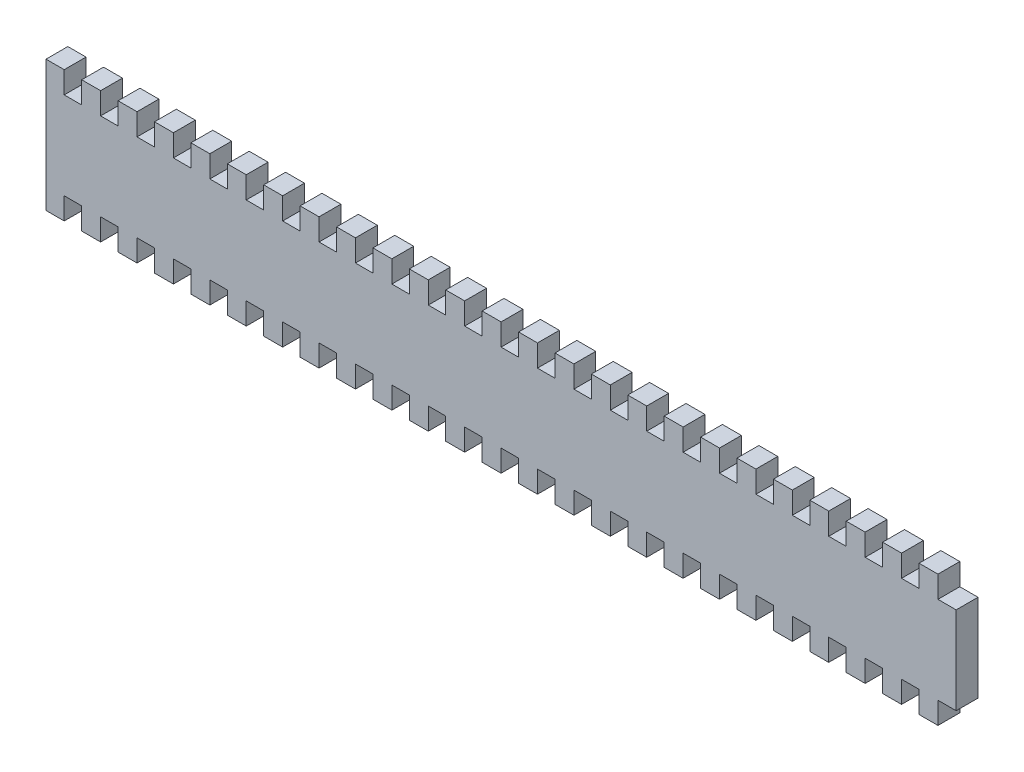
SolidWorks part; units mm, degrees
ref_plane "Plan de face" through (0, 0, 0) normal (0, 0, 1) x (1, 0, 0)
ref_plane "Plan de dessus" through (0, 0, 0) normal (0, 1, 0) x (1, 0, 0)
ref_plane "Plan de droite" through (0, 0, 0) normal (1, 0, 0) x (0, 0, -1)
sketch "Esquisse1" plane through (0, 0, 0) normal (0, 0, 1) x (1, 0, 0)
  line L0 (0, -18) -> (0, 18)
  line L1 (0, 18) -> (5.2, 18)
  line L2 (5.2, 18) -> (5.2, 12)
  line L3 (5.2, 12) -> (10, 12)
  line L4 (10, 12) -> (10, 18)
  line L5 (0, 0) -> (23.1965, 0) construction
  line L6 (10, 18) -> (15.2, 18)
  line L7 (15.2, 18) -> (15.2, 12)
  line L8 (15.2, 12) -> (20, 12)
  line L9 (20, 12) -> (20, 18)
  line L10 (20, 18) -> (25.2, 18)
  line L11 (25.2, 18) -> (25.2, 12)
  line L12 (25.2, 12) -> (30, 12)
  line L13 (30, 12) -> (30, 18)
  line L14 (30, 18) -> (35.2, 18)
  line L15 (35.2, 18) -> (35.2, 12)
  line L16 (35.2, 12) -> (40, 12)
  line L17 (40, 12) -> (40, 18)
  line L18 (40, 18) -> (45.2, 18)
  line L19 (45.2, 18) -> (45.2, 12)
  line L20 (45.2, 12) -> (50, 12)
  line L21 (50, 12) -> (50, 18)
  line L22 (50, 18) -> (55.2, 18)
  line L23 (55.2, 18) -> (55.2, 12)
  line L24 (55.2, 12) -> (60, 12)
  line L25 (60, 12) -> (60, 18)
  line L26 (60, 18) -> (65.2, 18)
  line L27 (65.2, 18) -> (65.2, 12)
  line L28 (65.2, 12) -> (70, 12)
  line L29 (70, 12) -> (70, 18)
  line L30 (70, 18) -> (75.2, 18)
  line L31 (75.2, 18) -> (75.2, 12)
  line L32 (75.2, 12) -> (80, 12)
  line L33 (80, 12) -> (80, 18)
  line L34 (80, 18) -> (85.2, 18)
  line L35 (85.2, 18) -> (85.2, 12)
  line L36 (85.2, 12) -> (90, 12)
  line L37 (90, 12) -> (90, 18)
  line L38 (90, 18) -> (95.2, 18)
  line L39 (95.2, 18) -> (95.2, 12)
  line L40 (95.2, 12) -> (100, 12)
  line L41 (100, 12) -> (100, 18)
  line L42 (100, 18) -> (105.2, 18)
  line L43 (105.2, 18) -> (105.2, 12)
  line L44 (105.2, 12) -> (110, 12)
  line L45 (110, 12) -> (110, 18)
  line L46 (110, 18) -> (115.2, 18)
  line L47 (115.2, 18) -> (115.2, 12)
  line L48 (115.2, 12) -> (120, 12)
  line L49 (120, 12) -> (120, 18)
  line L50 (120, 18) -> (125.2, 18)
  line L51 (125.2, 18) -> (125.2, 12)
  line L52 (125.2, 12) -> (130, 12)
  line L53 (130, 12) -> (130, 18)
  line L54 (130, 18) -> (135.2, 18)
  line L55 (135.2, 18) -> (135.2, 12)
  line L56 (135.2, 12) -> (140, 12)
  line L57 (140, 12) -> (140, 18)
  line L58 (140, 18) -> (145.2, 18)
  line L59 (145.2, 18) -> (145.2, 12)
  line L60 (145.2, 12) -> (150, 12)
  line L61 (150, 12) -> (150, 18)
  line L62 (150, 18) -> (155.2, 18)
  line L63 (155.2, 18) -> (155.2, 12)
  line L64 (155.2, 12) -> (160, 12)
  line L65 (160, 12) -> (160, 18)
  line L66 (160, 18) -> (165.2, 18)
  line L67 (165.2, 18) -> (165.2, 12)
  line L68 (165.2, 12) -> (170, 12)
  line L69 (170, 12) -> (170, 18)
  line L70 (170, 18) -> (175.2, 18)
  line L71 (175.2, 18) -> (175.2, 12)
  line L72 (175.2, 12) -> (180, 12)
  line L73 (180, 12) -> (180, 18)
  line L74 (180, 18) -> (185.2, 18)
  line L75 (185.2, 18) -> (185.2, 12)
  line L76 (185.2, 12) -> (190, 12)
  line L77 (190, 12) -> (190, 18)
  line L78 (190, 18) -> (195.2, 18)
  line L79 (195.2, 18) -> (195.2, 12)
  line L80 (195.2, 12) -> (200, 12)
  line L81 (200, 12) -> (200, 18)
  line L82 (200, 18) -> (205.2, 18)
  line L83 (205.2, 18) -> (205.2, 12)
  line L84 (205.2, 12) -> (210, 12)
  line L85 (210, 12) -> (210, 18)
  line L86 (210, 18) -> (215.2, 18)
  line L87 (215.2, 18) -> (215.2, 12)
  line L88 (215.2, 12) -> (220, 12)
  line L89 (220, 12) -> (220, 18)
  line L90 (220, 18) -> (225.2, 18)
  line L91 (225.2, 18) -> (225.2, 12)
  line L92 (225.2, 12) -> (230, 12)
  line L93 (230, 12) -> (230, 18)
  line L94 (230, 18) -> (235.2, 18)
  line L95 (235.2, 18) -> (235.2, 12)
  line L96 (235.2, 12) -> (240, 12)
  line L97 (240, 12) -> (240, 18)
  line L98 (240, 18) -> (245.2, 18)
  line L99 (245.2, 18) -> (245.2, 12)
  line L100 (245.2, 12) -> (250, 12)
  line L101 (250, 12) -> (250, -12)
  line L102 (250, 12) -> (250, 18) [skipped]
  line L103 (245.2, -12) -> (250, -12)
  line L104 (245.2, -18) -> (245.2, -12)
  line L105 (240, -18) -> (245.2, -18)
  line L106 (240, -12) -> (240, -18)
  line L107 (235.2, -12) -> (240, -12)
  line L108 (235.2, -18) -> (235.2, -12)
  line L109 (230, -18) -> (235.2, -18)
  line L110 (230, -12) -> (230, -18)
  line L111 (225.2, -12) -> (230, -12)
  line L112 (225.2, -18) -> (225.2, -12)
  line L113 (220, -18) -> (225.2, -18)
  line L114 (220, -12) -> (220, -18)
  line L115 (215.2, -12) -> (220, -12)
  line L116 (215.2, -18) -> (215.2, -12)
  line L117 (210, -18) -> (215.2, -18)
  line L118 (210, -12) -> (210, -18)
  line L119 (205.2, -12) -> (210, -12)
  line L120 (205.2, -18) -> (205.2, -12)
  line L121 (200, -18) -> (205.2, -18)
  line L122 (200, -12) -> (200, -18)
  line L123 (195.2, -12) -> (200, -12)
  line L124 (195.2, -18) -> (195.2, -12)
  line L125 (190, -18) -> (195.2, -18)
  line L126 (190, -12) -> (190, -18)
  line L127 (185.2, -12) -> (190, -12)
  line L128 (185.2, -18) -> (185.2, -12)
  line L129 (180, -18) -> (185.2, -18)
  line L130 (180, -12) -> (180, -18)
  line L131 (175.2, -12) -> (180, -12)
  line L132 (175.2, -18) -> (175.2, -12)
  line L133 (170, -18) -> (175.2, -18)
  line L134 (170, -12) -> (170, -18)
  line L135 (165.2, -12) -> (170, -12)
  line L136 (165.2, -18) -> (165.2, -12)
  line L137 (160, -18) -> (165.2, -18)
  line L138 (160, -12) -> (160, -18)
  line L139 (155.2, -12) -> (160, -12)
  line L140 (155.2, -18) -> (155.2, -12)
  line L141 (150, -18) -> (155.2, -18)
  line L142 (150, -12) -> (150, -18)
  line L143 (145.2, -12) -> (150, -12)
  line L144 (145.2, -18) -> (145.2, -12)
  line L145 (140, -18) -> (145.2, -18)
  line L146 (140, -12) -> (140, -18)
  line L147 (135.2, -12) -> (140, -12)
  line L148 (135.2, -18) -> (135.2, -12)
  line L149 (130, -18) -> (135.2, -18)
  line L150 (130, -12) -> (130, -18)
  line L151 (125.2, -12) -> (130, -12)
  line L152 (125.2, -18) -> (125.2, -12)
  line L153 (120, -18) -> (125.2, -18)
  line L154 (120, -12) -> (120, -18)
  line L155 (115.2, -12) -> (120, -12)
  line L156 (115.2, -18) -> (115.2, -12)
  line L157 (110, -18) -> (115.2, -18)
  line L158 (110, -12) -> (110, -18)
  line L159 (105.2, -12) -> (110, -12)
  line L160 (105.2, -18) -> (105.2, -12)
  line L161 (100, -18) -> (105.2, -18)
  line L162 (100, -12) -> (100, -18)
  line L163 (95.2, -12) -> (100, -12)
  line L164 (95.2, -18) -> (95.2, -12)
  line L165 (90, -18) -> (95.2, -18)
  line L166 (90, -12) -> (90, -18)
  line L167 (85.2, -12) -> (90, -12)
  line L168 (85.2, -18) -> (85.2, -12)
  line L169 (80, -18) -> (85.2, -18)
  line L170 (80, -12) -> (80, -18)
  line L171 (75.2, -12) -> (80, -12)
  line L172 (75.2, -18) -> (75.2, -12)
  line L173 (70, -18) -> (75.2, -18)
  line L174 (70, -12) -> (70, -18)
  line L175 (65.2, -12) -> (70, -12)
  line L176 (65.2, -18) -> (65.2, -12)
  line L177 (60, -18) -> (65.2, -18)
  line L178 (60, -12) -> (60, -18)
  line L179 (55.2, -12) -> (60, -12)
  line L180 (55.2, -18) -> (55.2, -12)
  line L181 (50, -18) -> (55.2, -18)
  line L182 (50, -12) -> (50, -18)
  line L183 (45.2, -12) -> (50, -12)
  line L184 (45.2, -18) -> (45.2, -12)
  line L185 (40, -18) -> (45.2, -18)
  line L186 (40, -12) -> (40, -18)
  line L187 (35.2, -12) -> (40, -12)
  line L188 (35.2, -18) -> (35.2, -12)
  line L189 (30, -18) -> (35.2, -18)
  line L190 (30, -12) -> (30, -18)
  line L191 (25.2, -12) -> (30, -12)
  line L192 (25.2, -18) -> (25.2, -12)
  line L193 (20, -18) -> (25.2, -18)
  line L194 (20, -12) -> (20, -18)
  line L195 (15.2, -12) -> (20, -12)
  line L196 (15.2, -18) -> (15.2, -12)
  line L197 (10, -18) -> (15.2, -18)
  line L198 (10, -12) -> (10, -18)
  line L199 (5.2, -12) -> (10, -12)
  line L200 (5.2, -18) -> (5.2, -12)
  line L201 (0, -18) -> (5.2, -18)
  point P10 (250, 0)
  dimension "D1" = 18
  dimension "D2" = 5.2
  dimension "D3" = 4.8
  dimension "D4" = 6
  dimension "D6" = 25
extrude "Boss.-Extru.1" add sketch "Esquisse1" along normal blind 6
sketch "Esquisse2" plane through (0, 0, 6) normal (0, 0, 1) x (1, 0, 0)
  line L0 (0, -18) -> (5.2, -18) construction
  line L1 (0, 18) -> (0.2, 18)
  line L2 (0, 18) -> (0, -18)
  line L3 (0, -18) -> (0.2, -18)
  line L4 (0.2, 18) -> (0.2, -18)
  dimension "D1" = 0.2
extrude "Enlèv. mat.-Extru.1" cut sketch "Esquisse2" against normal blind 10
sketch "Esquisse3" plane through (0, 0, 6) normal (0, 0, 1) x (1, 0, 0)
  line L1 (250, 12) -> (250.2, 12)
  line L2 (250, 12) -> (250, -12)
  line L3 (250, -12) -> (250.2, -12)
  line L4 (250.2, 12) -> (250.2, -12)
  dimension "D1" = 24
  dimension "D2" = 0.2
extrude "Boss.-Extru.2" add sketch "Esquisse3" against normal blind 6
